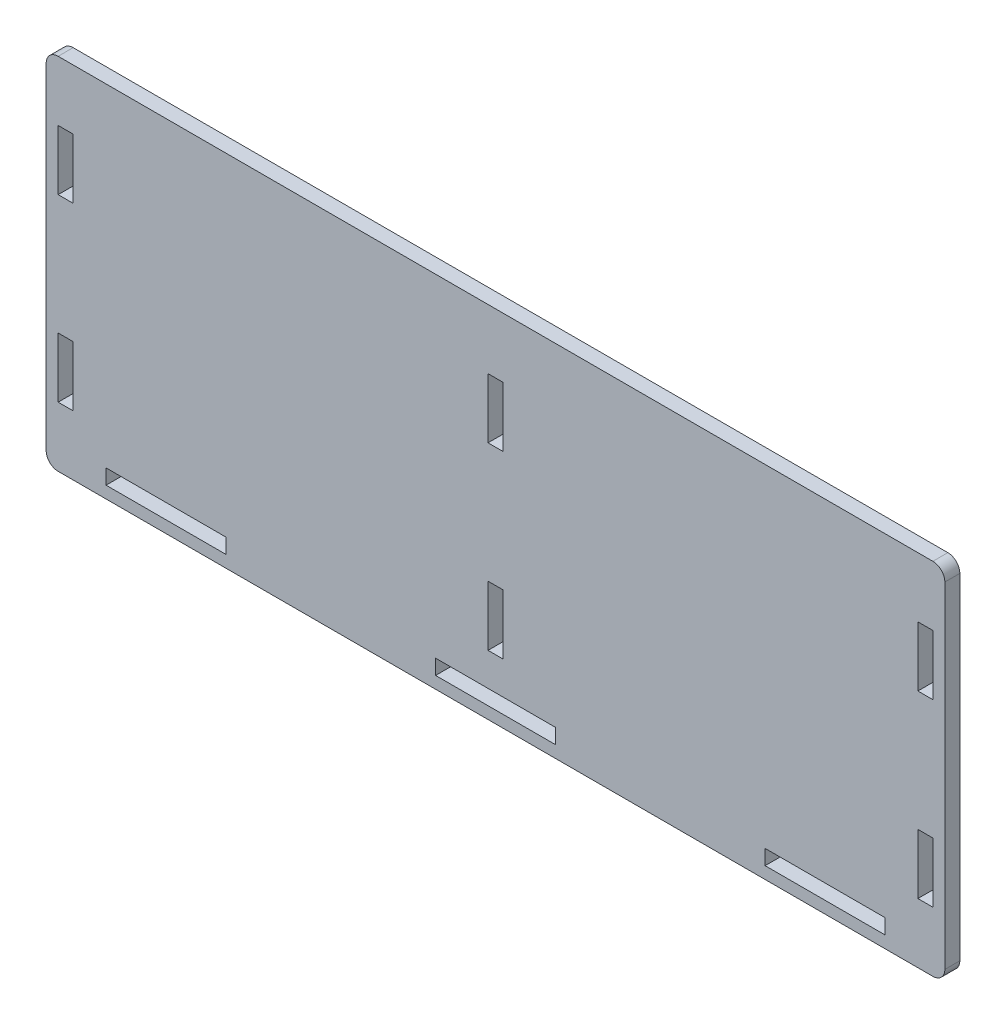
SolidWorks part; units mm, degrees
material "Mahogany"
ref_plane "Front Plane" through (0, 0, 0) normal (0, 0, 1) x (1, 0, 0)
ref_plane "Top Plane" through (0, 0, 0) normal (0, 1, 0) x (1, 0, 0)
ref_plane "Right Plane" through (0, 0, 0) normal (1, 0, 0) x (0, 0, -1)
sketch "Sketch1" plane through (0, 0, 0) normal (0, 0, 1) x (1, 0, 0)
  line L0 (0, 14.9925) -> (0, -14.4495) construction
  line L1 (-75, -30) -> (75, -30)
  line L2 (-75, -30) -> (-75, 30)
  line L3 (-75, 30) -> (75, 30)
  line L4 (75, -30) -> (75, 30)
  line L5 (-75, -30) -> (75, 30) construction
  line L6 (-75, 30) -> (75, -30) construction
  line L7 (-19.6788, 0) -> (23.9455, 0) construction
  line L8 (-73, -20) -> (-70.5, -20)
  line L9 (-73, 10) -> (-70.5, 10)
  line L10 (-73, 10) -> (-73, 20)
  line L11 (-73, 20) -> (-70.5, 20)
  line L12 (-70.5, 10) -> (-70.5, 20)
  line L13 (-73, 10) -> (-70.5, 20) construction
  line L14 (-73, 20) -> (-70.5, 10) construction
  line L15 (-70.5, -10) -> (-70.5, -20)
  line L16 (-73, -10) -> (-70.5, -10)
  line L17 (-73, -10) -> (-73, -20)
  line L18 (-1.25, 10) -> (-1.25, 20)
  line L19 (-1.25, 10) -> (1.25, 10)
  line L20 (1.25, 10) -> (1.25, 20)
  line L21 (-1.25, 20) -> (1.25, 20)
  line L22 (-1.25, -20) -> (1.25, -20)
  line L23 (1.25, -10) -> (1.25, -20)
  line L24 (-1.25, -10) -> (1.25, -10)
  line L25 (-1.25, -10) -> (-1.25, -20)
  line L26 (70.5, 10) -> (70.5, 20)
  line L27 (70.5, 10) -> (73, 10)
  line L28 (73, 10) -> (73, 20)
  line L29 (70.5, 20) -> (73, 20)
  line L30 (70.5, -20) -> (73, -20)
  line L31 (73, -10) -> (73, -20)
  line L32 (70.5, -10) -> (73, -10)
  line L33 (70.5, -10) -> (70.5, -20)
  line L34 (-10, -25.5) -> (-10, -28)
  line L35 (-65, -25.5) -> (-45, -25.5)
  line L36 (-65, -25.5) -> (-65, -28)
  line L37 (-65, -28) -> (-45, -28)
  line L38 (-45, -25.5) -> (-45, -28)
  line L39 (-65, -25.5) -> (-45, -28) construction
  line L40 (-65, -28) -> (-45, -25.5) construction
  line L41 (-10, -25.5) -> (10, -25.5)
  line L42 (10, -25.5) -> (10, -28)
  line L43 (-10, -28) -> (10, -28)
  line L44 (45, -25.5) -> (45, -28)
  line L45 (45, -25.5) -> (65, -25.5)
  line L46 (65, -25.5) -> (65, -28)
  line L47 (45, -28) -> (65, -28)
  point P0 (0, 0)
  point P10 (-71.75, 15)
  point P19 (-55, -26.75)
  point P40 (0, 0)
  dimension "D1" = 150
  dimension "D2" = 60
  dimension "D3" = 10
  dimension "D4" = 2.5
  dimension "D5" = 2
  dimension "D6" = 10
  dimension "D8" = 2
  dimension "D9" = 2
  dimension "D10" = 10
  dimension "D11" = 20
  dimension "D13" = 10
  dimension "D7" = 3
  dimension "D12" = 3
extrude "Boss-Extrude1" add sketch "Sketch1" along normal blind 2.5
fillet "Fillet2" radius 2 4 edges at (-75, -30, 1.25) (-75, 30, 1.25) (75, 30, 1.25) (75, -30, 1.25)
